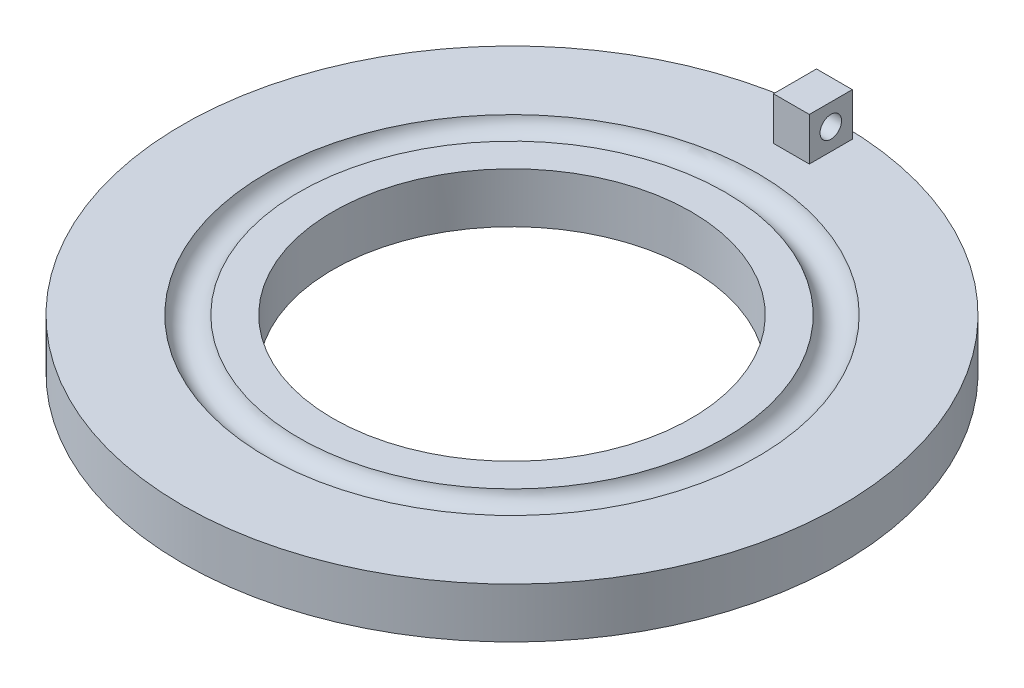
SolidWorks part; units mm, degrees
ref_plane "Front Plane" through (0, 0, 0) normal (0, 0, 1) x (1, 0, 0)
ref_plane "Top Plane" through (0, 0, 0) normal (0, 1, 0) x (1, 0, 0)
ref_plane "Right Plane" through (0, 0, 0) normal (1, 0, 0) x (0, 0, -1)
sketch "Sketch3" plane through (0, 0, 0) normal (0, 0, 1) x (1, 0, 0)
  line L0 (-70.0479, 3.5) -> (10.4298, 3.5) construction
  line L1 (0, 0) -> (-29.7294, 0)
  line L2 (0, 0) -> (0, 7)
  line L3 (0, 7) -> (-29.7294, 7)
  line L4 (-46, 0) -> (-46, 7)
  line L5 (-34.2706, 0) -> (-46, 0)
  line L6 (-34.2706, 7) -> (-46, 7)
  arc A0 (-29.7294, 0) -> (-34.2706, 0) centre (-32, -0.5) ccw
  arc A1 (-29.7294, 7) -> (-34.2706, 7) centre (-32, 7.5) cw
  point P9 (-46, 3.5)
  dimension "D3" = 4.65
  dimension "D1" = 46
  dimension "D2" = 7
  dimension "D4" = 32
  dimension "D5" = 0.5
revolve "Revolve1" add sketch "Sketch3" angle 360 about L2
sketch "Sketch4" plane through (0, 7, 0) normal (0, 1, 0) x (1, 0, 0)
  circle A0 centre (0, 0) radius 25
  dimension "D1" = 50
extrude "Cut-Extrude1" cut sketch "Sketch4" against normal through all both and the other way through all
sketch "Sketch5" plane through (0, 0, 0) normal (0, 1, 0) x (1, 0, 0)
  line L0 (-2.5, 45) -> (2.5, 39) construction
  line L1 (-2.5, 39) -> (2.5, 39)
  line L2 (-2.5, 39) -> (-2.5, 45)
  line L3 (-2.5, 45) -> (2.5, 45)
  line L4 (2.5, 39) -> (2.5, 45)
  line L5 (-2.5, 39) -> (2.5, 45) construction
  point P4 (0, 42)
  dimension "D1" = 42
  dimension "D2" = 6
  dimension "D3" = 5
extrude "Boss-Extrude1" add sketch "Sketch5" along normal blind 13
sketch "Sketch6" plane through (0, 0, 0) normal (1, 0, 0) x (0, 0, -1)
  line L0 (39, 13) -> (45, 7) construction
  line L1 (45, 13) -> (39, 13) construction
  line L2 (45, 7) -> (45, 13) construction
  line L3 (45, 13) -> (39, 7) construction
  circle A0 centre (42, 10) radius 1.5
  dimension "D1" = 3
extrude "Cut-Extrude2" cut sketch "Sketch6" against normal through all both and the other way through all
